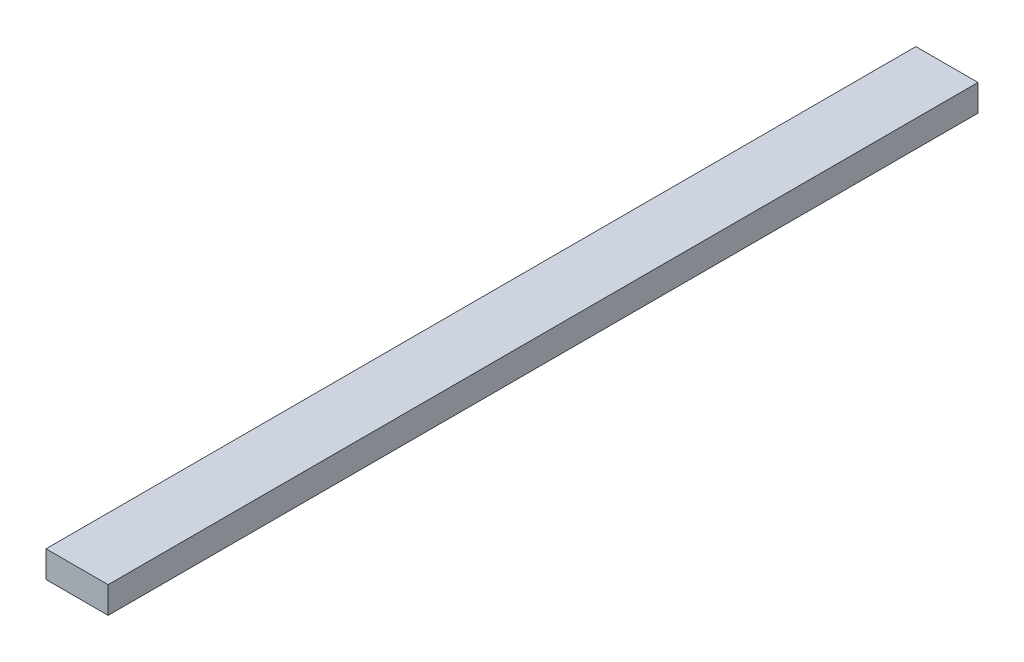
SolidWorks part; units mm, degrees
ref_plane "Front Plane" through (0, 0, 0) normal (0, 0, 1) x (1, 0, 0)
ref_plane "Top Plane" through (0, 0, 0) normal (0, 1, 0) x (1, 0, 0)
ref_plane "Right Plane" through (0, 0, 0) normal (1, 0, 0) x (0, 0, -1)
sketch "Sketch1" plane through (0, 0, 0) normal (0, 0, 1) x (1, 0, 0)
  line L1 (44.45, 19.05) -> (-44.45, 19.05)
  line L2 (44.45, 19.05) -> (44.45, -19.05)
  line L3 (44.45, -19.05) -> (-44.45, -19.05)
  line L4 (-44.45, 19.05) -> (-44.45, -19.05)
  line L5 (44.45, 19.05) -> (-44.45, -19.05) construction
  line L6 (44.45, -19.05) -> (-44.45, 19.05) construction
  point P0 (0, 0)
  dimension "D1" = 88.9
  dimension "D2" = 38.1
extrude "Boss-Extrude1" add sketch "Sketch1" along normal mid plane 1244.6
